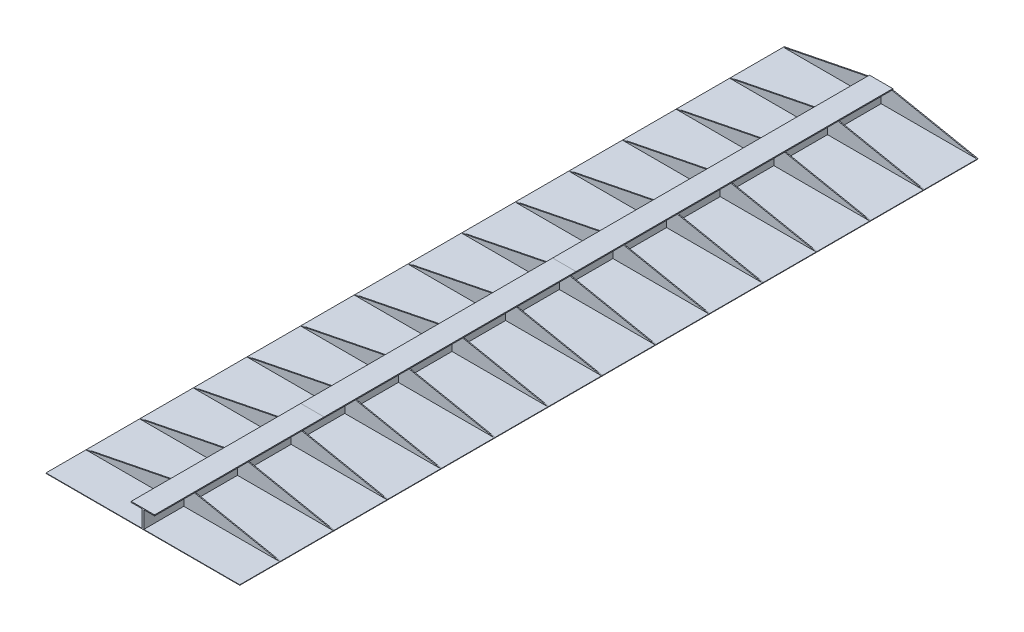
SolidWorks part; units mm, degrees
material "6061-T6 (SS)"
ref_plane "Front Plane" through (0, 0, 0) normal (0, 0, 1) x (1, 0, 0)
ref_plane "Top Plane" through (0, 0, 0) normal (0, 1, 0) x (1, 0, 0)
ref_plane "Right Plane" through (0, 0, 0) normal (1, 0, 0) x (0, 0, -1)
sketch "Sketch1" plane through (0, 0, 0) normal (0, 0, 1) x (1, 0, 0)
  line L0 (-90, 185.5) -> (151.3, 185.5)
  line L1 (151.3, 185.5) -> (151.3, 0)
  line L2 (151.3, 0) -> (1030.65, 0)
  line L3 (1030.65, 0) -> (1030.65, -5)
  line L4 (1030.65, -5) -> (-969.35, -5)
  line L5 (-969.35, -5) -> (-969.35, 0)
  line L6 (-969.35, 0) -> (-90, 0)
  line L7 (-90, 0) -> (-90, 185.5)
  dimension "D1" = 190.5
  dimension "D2" = 241.3
  dimension "D3" = 90
  dimension "D4" = 5
  dimension "D5" = 2000
extrude "Boss-Extrude1" add sketch "Sketch1" against normal blind 7620
sketch "Sketch7" plane through (0, 0, -7620) normal (0, 0, -1) x (-1, 0, 0)
  line L0 (-151.3, 0) -> (-151.3, 185.5) construction
  line L1 (-151.3, 175.5) -> (-40.65, 175.5)
  line L2 (-151.3, 175.5) -> (-151.3, 0)
  line L3 (-151.3, 0) -> (-40.65, 0)
  line L4 (-40.65, 175.5) -> (-40.65, 0)
  line L5 (-151.3, 185.5) -> (90, 185.5) construction
  line L6 (969.35, -5) -> (-1030.65, -5) construction
  line L7 (90, 185.5) -> (90, 0) construction
  line L8 (90, 175.5) -> (-20.65, 175.5)
  line L9 (90, 175.5) -> (90, 0)
  line L10 (90, 0) -> (-20.65, 0)
  line L11 (-20.65, 175.5) -> (-20.65, 0)
  dimension "D1" = 10
  dimension "D2" = 5
  dimension "D3" = 20
extrude "Cut-Extrude3" cut sketch "Sketch7" against normal through all
ref_plane "Plane1" through (30.65, 0, 0) normal (1, 0, 0) x (0, 0, -1)
sketch "Sketch8" plane through (0, 0, -7620) normal (0, 0, -1) x (-1, 0, 0)
  line L0 (-40.65, 0) -> (-40.65, 175.5)
  line L1 (-40.65, 175.5) -> (-151.3, 175.5)
  line L2 (-151.3, 175.5) -> (-1030.65, 0)
  line L3 (-1030.65, 0) -> (-40.65, 0)
extrude "Boss-Extrude3" add sketch "Sketch8" against normal blind 9.525
pattern_linear "LPattern2" count 14 spacing 553.68 along (0, 0, 1) of "Boss-Extrude3"
mirror "Mirror2" about plane through (30.65, 0, 0) normal (1, 0, 0) of "LPattern2", "Boss-Extrude3"
sketch "Sketch9" plane through (0, 185.5, 0) normal (0, 1, 0) x (1, 0, 0)
  line L0 (151.3, 7620) -> (151.3, 0) construction
  line L1 (151.3, 1750) -> (-90, 1750)
  line L2 (151.3, 1750) -> (151.3, 4350)
  line L3 (151.3, 4350) -> (-90, 4350)
  line L4 (-90, 1750) -> (-90, 4350)
  line L5 (-90, 7620) -> (-90, 0) construction
  line L6 (151.3, 0) -> (-90, 0) construction
  dimension "D1" = 2600
  dimension "D2" = 1750
split line "Split Line2"
